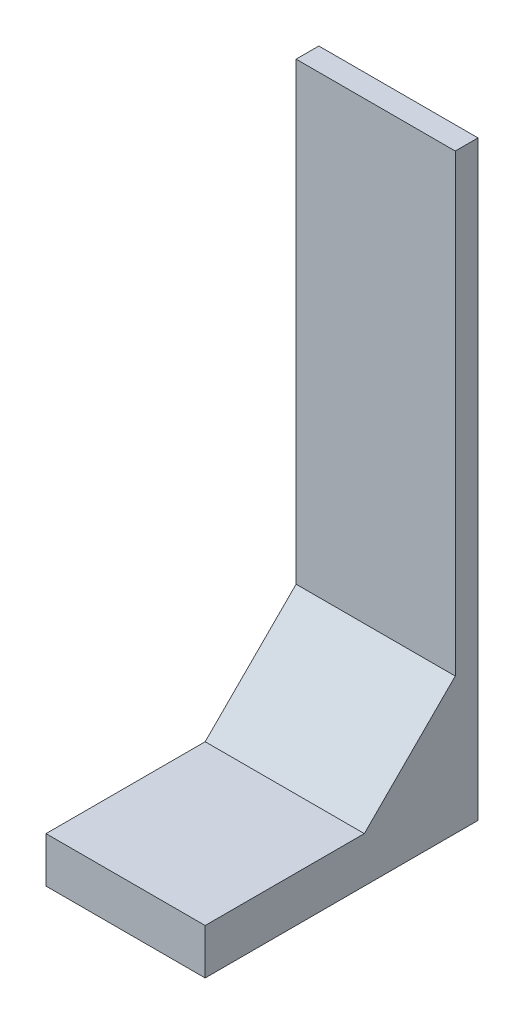
SolidWorks part; units mm, degrees
ref_plane "Front Plane" through (0, 0, 0) normal (0, 0, 1) x (1, 0, 0)
ref_plane "Top Plane" through (0, 0, 0) normal (0, 1, 0) x (1, 0, 0)
ref_plane "Right Plane" through (0, 0, 0) normal (1, 0, 0) x (0, 0, -1)
sketch "Sketch1" plane through (0, 0, 0) normal (1, 0, 0) x (0, 0, -1)
  line L0 (0, 0) -> (0, 165.1)
  line L1 (0, 0) -> (-76.2, 0)
  line L2 (-76.2, 0) -> (-76.2, 12.7)
  line L3 (0, 165.1) -> (-6.35, 165.1)
  line L4 (-6.35, 165.1) -> (-6.35, 12.7)
  line L5 (-6.35, 12.7) -> (-76.2, 12.7)
  dimension "D1" = 165.1
  dimension "D2" = 76.2
  dimension "D3" = 12.7
  dimension "D4" = 6.35
extrude "Boss-Extrude1" add sketch "Sketch1" along normal mid plane 44.45
chamfer "Chamfer1" distance 25.4 angle 45 1 edges at (0, 12.7, 6.35)
